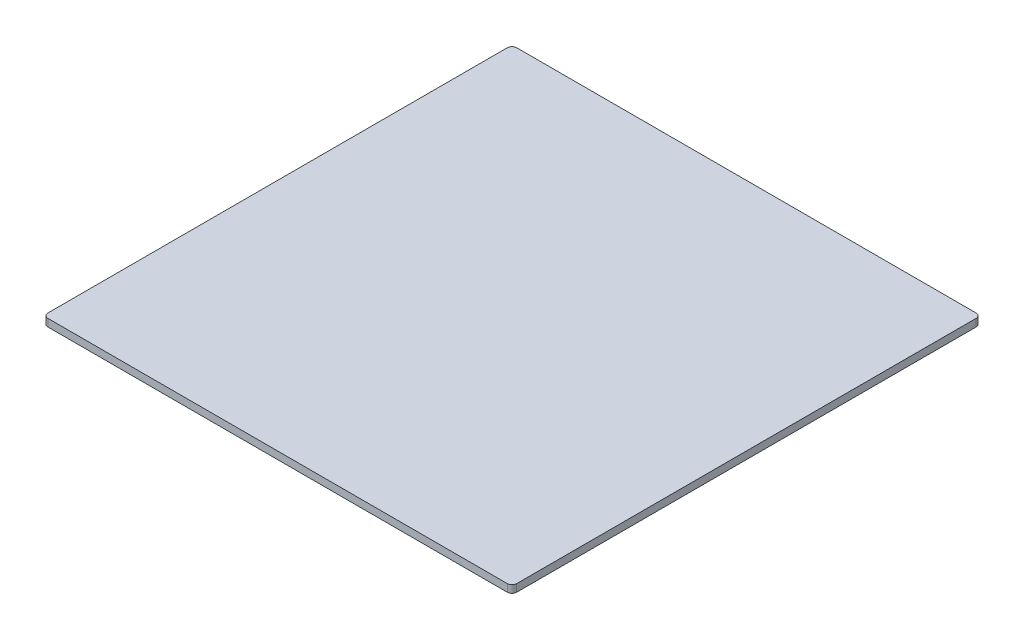
SolidWorks part; units mm, degrees
material "Kapton"
ref_plane "Front Plane" through (0, 0, 0) normal (0, 0, 1) x (1, 0, 0)
ref_plane "Top Plane" through (0, 0, 0) normal (0, 1, 0) x (1, 0, 0)
ref_plane "Right Plane" through (0, 0, 0) normal (1, 0, 0) x (0, 0, -1)
sketch "Sketch1" plane through (0, 0, 0) normal (0, 1, 0) x (1, 0, 0)
  line L1 (-50, -50) -> (50, -50)
  line L2 (-50, -50) -> (-50, 50)
  line L3 (-50, 50) -> (50, 50)
  line L4 (50, -50) -> (50, 50)
  line L5 (-50, -50) -> (50, 50) construction
  line L6 (-50, 50) -> (50, -50) construction
  point P0 (0, 0)
  dimension "D1" = 100
extrude "Boss-Extrude1" add sketch "Sketch1" along normal mid plane 1.6
fillet "Fillet1" radius 1 4 edges at (50, 0, 50) (-50, 0, -50) (50, 0, -50) (-50, 0, 50)
sketch "Sketch2" plane through (0, 0.8, 0) normal (0, 1, 0) x (1, 0, 0)
  text T0 "POWER SUPPLY PCB\r\nNO COMPONENTS CUZ IM LAZY AF, \r\nBUT TRUST ME THEY FIT"
sketch "Sketch3" plane through (0, -0.8, 0) normal (0, -1, 0) x (1, 0, 0)
  line L1 (48, 48) -> (-48, 48)
  line L2 (48, 48) -> (48, -48)
  line L3 (48, -48) -> (-48, -48)
  line L4 (-48, 48) -> (-48, -48)
  line L5 (48, 48) -> (-48, -48) construction
  line L6 (48, -48) -> (-48, 48) construction
  arc A0 (-48, -39.8683) -> (-39.8683, -48) centre (-43.9341, -43.9341) ccw construction
  point P0 (0, 0)
